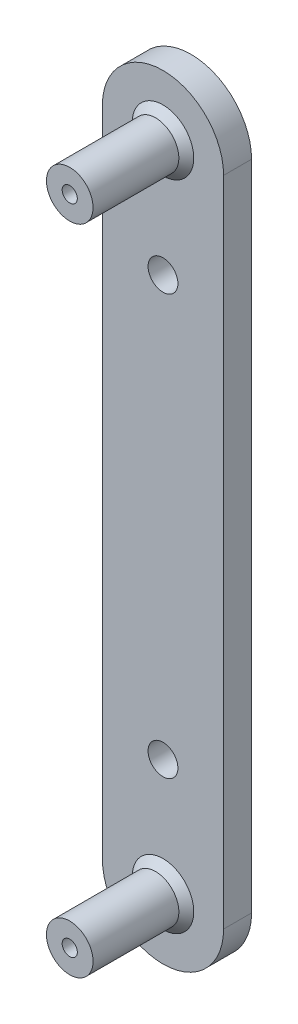
SolidWorks part; units mm, degrees
ref_plane "Front Plane" through (0, 0, 0) normal (1, 0, 0) x (0, 1, 0)
ref_plane "Top Plane" through (0, 0, 0) normal (0, 0, 1) x (0, 1, 0)
ref_plane "Right Plane" through (0, 0, 0) normal (0, 1, 0) x (-1, 0, 0)
sketch "Sketch1" plane through (0, 0, 0) normal (0, 0, 1) x (0, 1, 0)
  line L0 (-35, 0) -> (35, 0) construction
  line L1 (-35, 2.5) -> (35, 2.5)
  line L2 (-35, -2.5) -> (35, -2.5)
  arc A0 (-35, 2.5) -> (-35, -2.5) centre (-35, 0) ccw
  arc A1 (35, -2.5) -> (35, 2.5) centre (35, 0) ccw
  circle A2 centre (-35, 0) radius 2.5
  circle A3 centre (35, 0) radius 2.5
  point P2 (0, 0)
  dimension "D1" = 5
  dimension "D2" = 70
extrude "Boss-Extrude1" add sketch "Sketch1" along normal blind 10
sketch "Sketch2" plane through (0, 0, 0) normal (0, 0, -1) x (1, 0, 0)
  line L0 (0, 35) -> (0, -35) construction
  line L1 (6.5, 35) -> (6.5, -35)
  line L2 (-6.5, 35) -> (-6.5, -35)
  arc A0 (6.5, 35) -> (-6.5, 35) centre (0, 35) ccw
  arc A1 (-6.5, -35) -> (6.5, -35) centre (0, -35) ccw
  circle A2 centre (0, -35) radius 2.5 construction
  point P4 (0, 0)
  dimension "D1" = 4
extrude "Boss-Extrude2" add sketch "Sketch2" along normal blind 3
sketch "Sketch3" plane through (0, 0, 10) normal (0, 0, 1) x (1, 0, 0)
  circle A0 centre (0, -35) radius 0.8125
  circle A1 centre (0, 35) radius 0.8125
  dimension "D1" = 1.625
extrude "Cut-Extrude1" cut sketch "Sketch3" against normal blind 18
chamfer "Chamfer1" distance 0.8 angle 45 2 edges at (-2.5, 35, 0) (2.5, -35, 0)
sketch "Sketch4" plane through (0, 0, 0) normal (0, 0, 1) x (1, 0, 0)
  line L0 (0, -22.5) -> (0, 22.5)
  line L1 (0, 0) -> (17.8408, 0) construction
  circle A0 centre (0, 22.5) radius 1.6
  circle A1 centre (0, -22.5) radius 1.6
  point P4 (0, 0)
  dimension "D1" = 3.2
  dimension "D2" = 22.5
extrude "Cut-Extrude2" cut sketch "Sketch4" against normal blind 10 contours A1 | A0
equation "\"D2@Sketch4\"=45/2"
